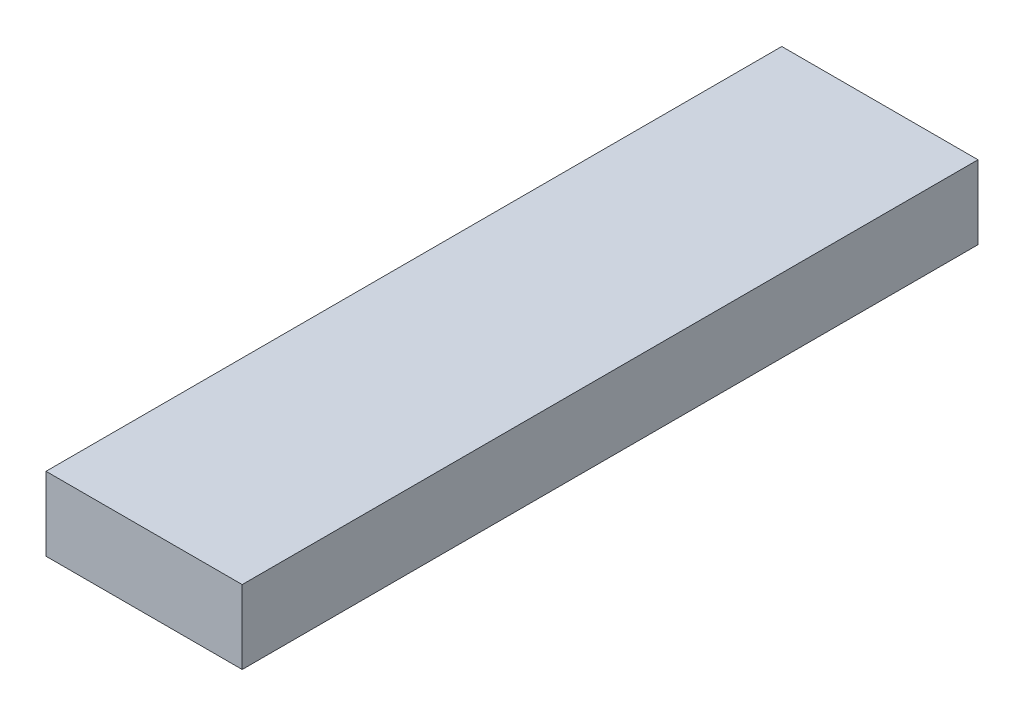
SolidWorks part; units mm, degrees
material "SBR"
ref_plane "Front Plane" through (0, 0, 0) normal (0, 0, 1) x (1, 0, 0)
ref_plane "Top Plane" through (0, 0, 0) normal (0, 1, 0) x (1, 0, 0)
ref_plane "Right Plane" through (0, 0, 0) normal (1, 0, 0) x (0, 0, -1)
sketch "Sketch1" plane through (0, 0, 0) normal (0, 0, 1) x (1, 0, 0)
  line L1 (0, 0) -> (25.4, 0)
  line L2 (0, 0) -> (0, 9.525)
  line L3 (0, 9.525) -> (25.4, 9.525)
  line L4 (25.4, 0) -> (25.4, 9.525)
  dimension "D1" = 25.4
  dimension "D2" = 9.525
extrude "Boss-Extrude1" add sketch "Sketch1" along normal blind 95.25
